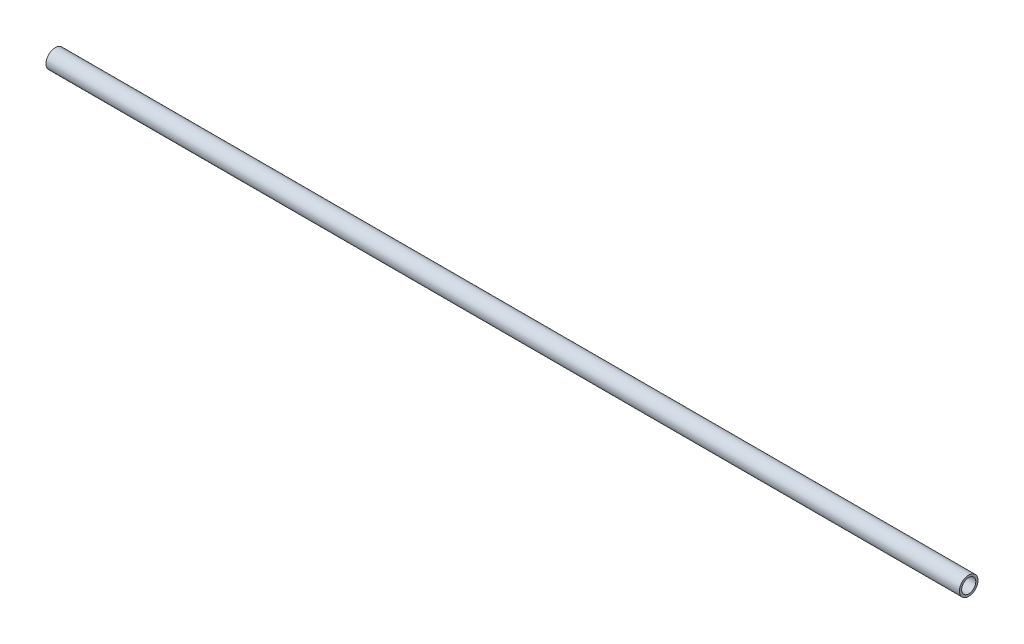
SolidWorks part; units mm, degrees
material "AISI 4130 Steel, annealed at 865C"
ref_plane "Front Plane" through (0, 0, 0) normal (0, 0, 1) x (1, 0, 0)
ref_plane "Top Plane" through (0, 0, 0) normal (0, 1, 0) x (1, 0, 0)
ref_plane "Right Plane" through (0, 0, 0) normal (1, 0, 0) x (0, 0, -1)
sketch "Sketch1" plane through (0, 0, 0) normal (1, 0, 0) x (0, 0, -1)
  circle A0 centre (0, 0) radius 12.7
  circle A1 centre (0, 0) radius 9.652
  dimension "D1" = 25.4
  dimension "D2" = 19.304
extrude "Boss-Extrude1" add sketch "Sketch1" along normal blind 1250
